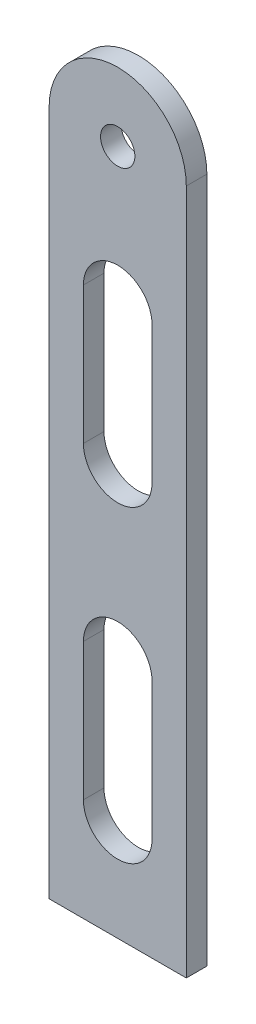
SolidWorks part; units mm, degrees
ref_plane "Front Plane" through (0, 0, 0) normal (0, 0, 1) x (1, 0, 0)
ref_plane "Top Plane" through (0, 0, 0) normal (0, 1, 0) x (1, 0, 0)
ref_plane "Right Plane" through (0, 0, 0) normal (1, 0, 0) x (0, 0, -1)
sketch "Sketch1" plane through (0, 0, 0) normal (0, 0, 1) x (1, 0, 0)
  line L0 (0, 0) -> (0, -90) construction
  line L1 (10, 0) -> (10, -100)
  line L2 (-10, 0) -> (-10, -100)
  line L3 (-10, -100) -> (10, -100)
  line L9 (0, -20) -> (0, -40) construction
  line L10 (5, -20) -> (5, -40)
  line L11 (-5, -20) -> (-5, -40)
  line L12 (0, -85) -> (0, -65) construction
  line L13 (-5, -85) -> (-5, -65)
  line L14 (5, -85) -> (5, -65)
  arc A0 (10, 0) -> (-10, 0) centre (0, 0) ccw
  arc A2 (5, -20) -> (-5, -20) centre (0, -20) ccw
  arc A3 (-5, -40) -> (5, -40) centre (0, -40) ccw
  arc A4 (-5, -85) -> (5, -85) centre (0, -85) ccw
  arc A5 (5, -65) -> (-5, -65) centre (0, -65) ccw
  circle A6 centre (0, 0) radius 2.5
  point P3 (0, -50)
  point P26 (0, -30)
  point P33 (0, -75)
  dimension "D1" = 100
extrude "Boss-Extrude1" add sketch "Sketch1" along normal blind 3
